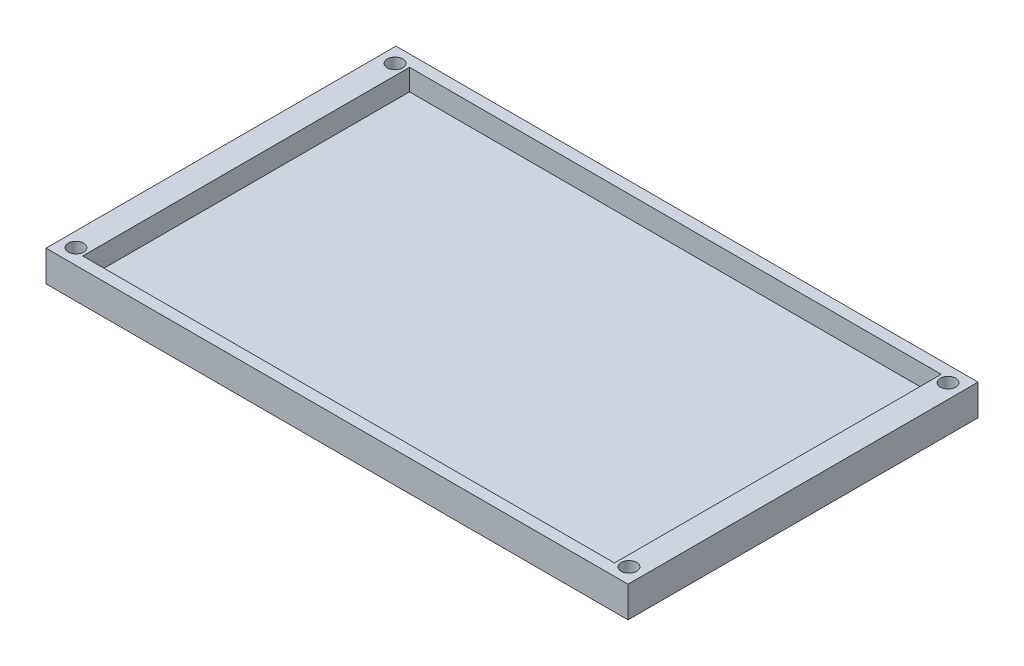
SolidWorks part; units mm, degrees
material "ABS"
ref_plane "Front Plane" through (0, 0, 0) normal (0, 0, 1) x (1, 0, 0)
ref_plane "Top Plane" through (0, 0, 0) normal (0, 1, 0) x (1, 0, 0)
ref_plane "Right Plane" through (0, 0, 0) normal (1, 0, 0) x (0, 0, -1)
other "Configuration Table"
sketch "Sketch1" plane through (0, 0, 0) normal (0, 1, 0) x (1, 0, 0)
  line L1 (-75.25, -45.25) -> (75.25, -45.25)
  line L2 (-75.25, -45.25) -> (-75.25, 45.25)
  line L3 (-75.25, 45.25) -> (75.25, 45.25)
  line L4 (75.25, -45.25) -> (75.25, 45.25)
  line L5 (-75.25, -45.25) -> (75.25, 45.25) construction
  line L6 (-75.25, 45.25) -> (75.25, -45.25) construction
  line L11 (68.9595, -41.4674) -> (-68.9595, 41.4674) construction
  line L12 (69, 41.4) -> (-69, -41.4) construction
  line L13 (68.75, -42.25) -> (-68.75, -42.25)
  line L14 (68.75, -42.25) -> (68.75, 42.25)
  line L15 (68.75, 42.25) -> (-68.75, 42.25)
  line L16 (-68.75, -42.25) -> (-68.75, 42.25)
  line L17 (68.75, -42.25) -> (-68.75, 42.25) construction
  line L18 (68.75, 42.25) -> (-68.75, -42.25) construction
  point P0 (0, 0)
  point P5 (0, 0)
  point P11 (0, 0)
  dimension "D1" = 90.5
  dimension "D2" = 150.5
  dimension "D3" = 6.5
  dimension "D4" = 3
extrude "Boss-Extrude1" add sketch "Sketch1" along normal blind 8
sketch "Sketch2" plane through (0, 8, 0) normal (0, 1, 0) x (1, 0, 0)
  line L1 (71.5, -41.25) -> (-71.5, -41.25) construction
  line L2 (71.5, -41.25) -> (71.5, 41.25) construction
  line L3 (71.5, 41.25) -> (-71.5, 41.25) construction
  line L4 (-71.5, -41.25) -> (-71.5, 41.25) construction
  line L5 (71.5, -41.25) -> (-71.5, 41.25) construction
  line L6 (71.5, 41.25) -> (-71.5, -41.25) construction
  circle A0 centre (-71.5, 41.25) radius 2
  circle A1 centre (-71.5, -41.25) radius 2
  circle A2 centre (71.5, -41.25) radius 2
  circle A3 centre (71.5, 41.25) radius 2
  point P0 (0, 0)
  dimension "D3" = 4
  dimension "D4" = 4
  dimension "D5" = 4
  dimension "D6" = 4
  dimension "D1" = 82.5
  dimension "D2" = 143
extrude "Cut-Extrude1" cut sketch "Sketch2" against normal blind 39
sketch "Sketch3" plane through (-68.75, 0, 0) normal (1, 0, 0) x (0, 0, -1)
  line L0 (42.25, 8) -> (42.25, 0) construction
  line L1 (-42.25, 0) -> (42.25, 0)
  line L2 (-42.25, 0) -> (-42.25, 2.5)
  line L3 (-42.25, 2.5) -> (42.25, 2.5)
  line L4 (42.25, 0) -> (42.25, 2.5)
  dimension "D1" = 2.5
extrude "Boss-Extrude2" add sketch "Sketch3" along normal blind 138
